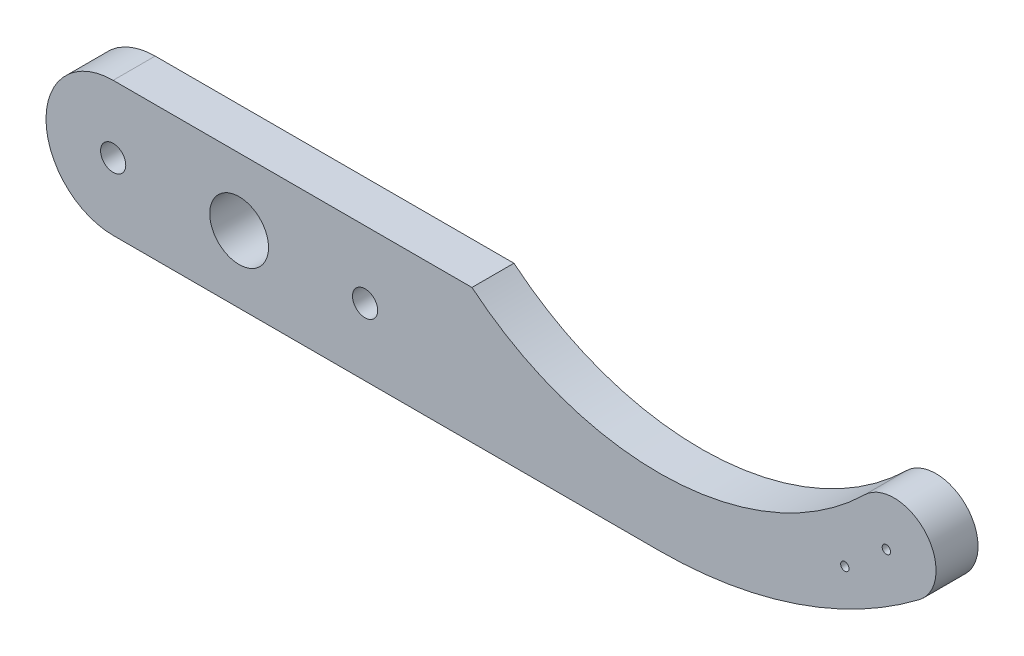
SolidWorks part; units mm, degrees
ref_plane "Plan de face" through (0, 0, 0) normal (0, 0, 1) x (1, 0, 0)
ref_plane "Plan de dessus" through (0, 0, 0) normal (0, 1, 0) x (1, 0, 0)
ref_plane "Plan de droite" through (0, 0, 0) normal (1, 0, 0) x (0, 0, -1)
sketch "Esquisse1" plane through (0, 0, 0) normal (0, 0, 1) x (1, 0, 0)
  line L0 (0, 0) -> (80, 0) construction
  line L1 (20, 0) -> (20, 23.8674) construction
  line L2 (0, 0) -> (0, 35) construction
  line L3 (0, 35) -> (50, 35) construction
  line L4 (0, 8) -> (20, 8)
  line L5 (74.5, 10.005) -> (78, 6.4343) construction
  line L6 (20, 8) -> (27.7289, 8)
  line L7 (0, -8) -> (50, -8)
  line L8 (50, 35) -> (50, -8) construction
  line L9 (0, 8) -> (-15, 8)
  line L10 (0, 0) -> (-15, 0) construction
  line L11 (0, -8) -> (-15, -8)
  line L12 (78, 6.4343) -> (77.0843, 5.6542) construction
  line L13 (72.1363, 1.4391) -> (77.0843, 5.6542) construction
  circle A0 centre (77.0843, 5.6542) radius 0.5
  arc A1 (0, 8) -> (0, -8) centre (0, 0) ccw construction
  circle A2 centre (50, 35) radius 35 construction
  arc A3 (27.7289, 8) -> (74.5, 10.005) centre (50, 35) ccw
  arc A4 (74.5, 10.005) -> (81.0259, 2.4538) centre (78, 6.4343) cw
  arc A5 (50, -8) -> (81.0259, 2.4538) centre (50, 43.2677) ccw
  circle A6 centre (15, 0) radius 1.5
  arc A7 (-15, 8) -> (-15, -8) centre (-15, 0) ccw
  circle A8 centre (-15, 0) radius 1.5
  circle A9 centre (0, 0) radius 3.5
  circle A10 centre (72.1363, 1.4391) radius 0.5
  dimension "D3" = 3
  dimension "D4" = 35
  dimension "D6" = 70
  dimension "D7" = 5
  dimension "D8" = 8
  dimension "D9" = 28
  dimension "D10" = 15
  dimension "D11" = 8
  dimension "D13" = 3
  dimension "D14" = 7
  dimension "D15" = 1.2
  dimension "D17" = 1
  dimension "D18" = 6.5
  dimension "D1" = 20
  dimension "D2" = 80
  dimension "D5" = 50
  dimension "D12" = 15
  dimension "D16" = 86
extrude "Boss.-Extru.1" add sketch "Esquisse1" along normal blind 5
